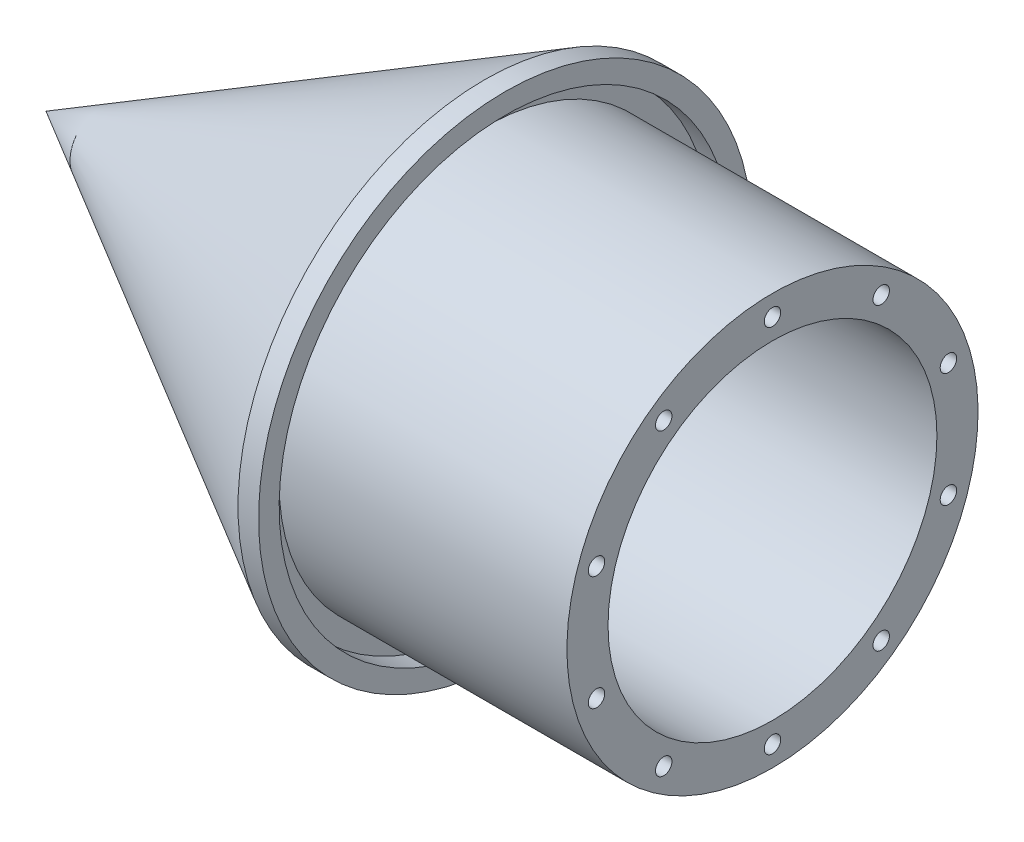
SolidWorks part; units mm, degrees
ref_plane "Front Plane" through (0, 0, 0) normal (0, 0, 1) x (1, 0, 0)
ref_plane "Top Plane" through (0, 0, 0) normal (0, 1, 0) x (1, 0, 0)
ref_plane "Right Plane" through (0, 0, 0) normal (1, 0, 0) x (0, 0, -1)
sketch "Sketch1" plane through (0, 0, 0) normal (0, 0, 1) x (1, 0, 0)
  line L0 (-123.8895, 0) -> (97.0861, 0) construction
  line L1 (0, 0) -> (0, 40)
  line L14 (0, 40) -> (0, 50)
  line L15 (0, 40) -> (-80, 40)
  line L16 (-80, 40) -> (-80, 45)
  line L18 (0, 50) -> (-70, 50)
  line L19 (-70, 50) -> (-70, 55)
  line L20 (-70, 55) -> (-65, 55)
  line L21 (-65, 55) -> (-65, 60)
  line L22 (-65, 60) -> (-70, 60)
  line L23 (-160, 0) -> (-80, 45)
  line L24 (-160, 0) -> (-176.7005, 0)
  line L25 (-70, 60) -> (-176.7005, 0)
  point P4 (0, 0)
  dimension "D1" = 176.7005
  dimension "D2" = 40
  dimension "D3" = 5
  dimension "D4" = 80
  dimension "D5" = 10
  dimension "D6" = 70
  dimension "D7" = 5
  dimension "D8" = 5
revolve "Revolve2" add sketch "Sketch1" angle 360 about L0
sketch "Sketch2" plane through (0, 0, 0) normal (1, 0, 0) x (0, 0, -1)
  circle A0 centre (0, 45) radius 2
  dimension "D1" = 4
  dimension "D2" = 45
extrude "Cut-Extrude1" cut sketch "Sketch2" against normal blind 20
pattern_circular "CirPattern1" count 10 over 360 about axis through (0, 0, 0) along (1, 0, 0) of "Cut-Extrude1"
